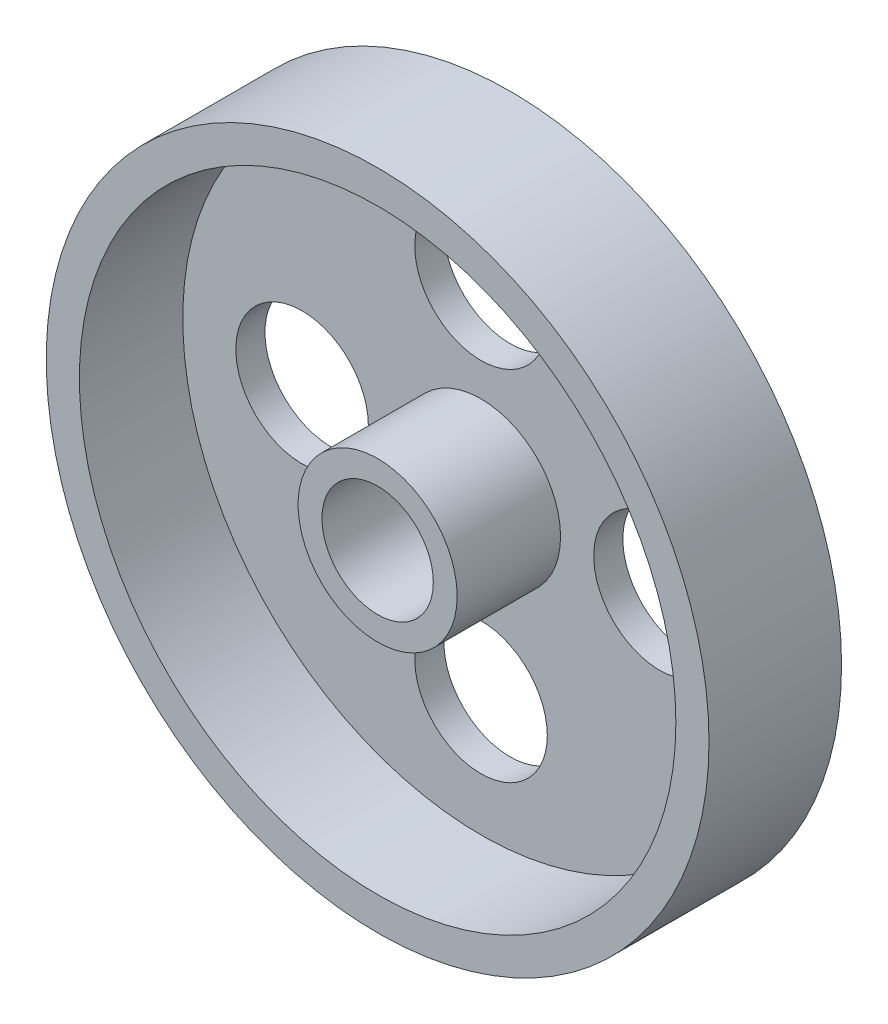
SolidWorks part; units mm, degrees
ref_plane "Front Plane" through (0, 0, 0) normal (0, 0, 1) x (1, 0, 0)
ref_plane "Top Plane" through (0, 0, 0) normal (0, 1, 0) x (1, 0, 0)
ref_plane "Right Plane" through (0, 0, 0) normal (1, 0, 0) x (0, 0, -1)
sketch "Sketch1" plane through (0, 0, 0) normal (0, 0, 1) x (1, 0, 0)
  circle A0 centre (0, 0) radius 25
extrude "Wheel_Web_50mm" add sketch "Sketch1" along normal blind 2.2 from offset 0
sketch "Sketch2" plane through (0, 0, 0) normal (0, 0, 1) x (1, 0, 0)
  circle A0 centre (0, 0) radius 25
  circle A1 centre (0, 0) radius 22.5
extrude "Outer_Rim_10mm_Wide" add sketch "Sketch2" along normal blind 7.8 from offset 2.2
sketch "Sketch3" plane through (0, 0, 0) normal (0, 0, 1) x (1, 0, 0)
  circle A0 centre (0, 0) radius 6
extrude "Hub_12mm" add sketch "Sketch3" along normal blind 7.8 from offset 2.2
sketch "Sketch4" plane through (0, 0, 0) normal (0, 0, 1) x (1, 0, 0)
  circle A0 centre (0, 0) radius 4.2
extrude "Axle_Bore_FIT_CHECK" cut sketch "Sketch4" along normal blind 10.2 from offset 0.1
sketch "Sketch5" plane through (0, 0, 0) normal (0, 0, 1) x (1, 0, 0)
  circle A0 centre (-13.5, 0) radius 5
extrude "Lightening_X_-13.5" cut sketch "Sketch5" along normal blind 10.2 from offset 0.1
sketch "Sketch6" plane through (0, 0, 0) normal (0, 0, 1) x (1, 0, 0)
  circle A0 centre (13.5, 0) radius 5
extrude "Lightening_X_13.5" cut sketch "Sketch6" along normal blind 10.2 from offset 0.1
sketch "Sketch7" plane through (0, 0, 0) normal (0, 0, 1) x (1, 0, 0)
  circle A0 centre (0, -13.5) radius 5
extrude "Lightening_Y_-13.5" cut sketch "Sketch7" along normal blind 10.2 from offset 0.1
sketch "Sketch8" plane through (0, 0, 0) normal (0, 0, 1) x (1, 0, 0)
  circle A0 centre (0, 13.5) radius 5
extrude "Lightening_Y_13.5" cut sketch "Sketch8" along normal blind 10.2 from offset 0.1
